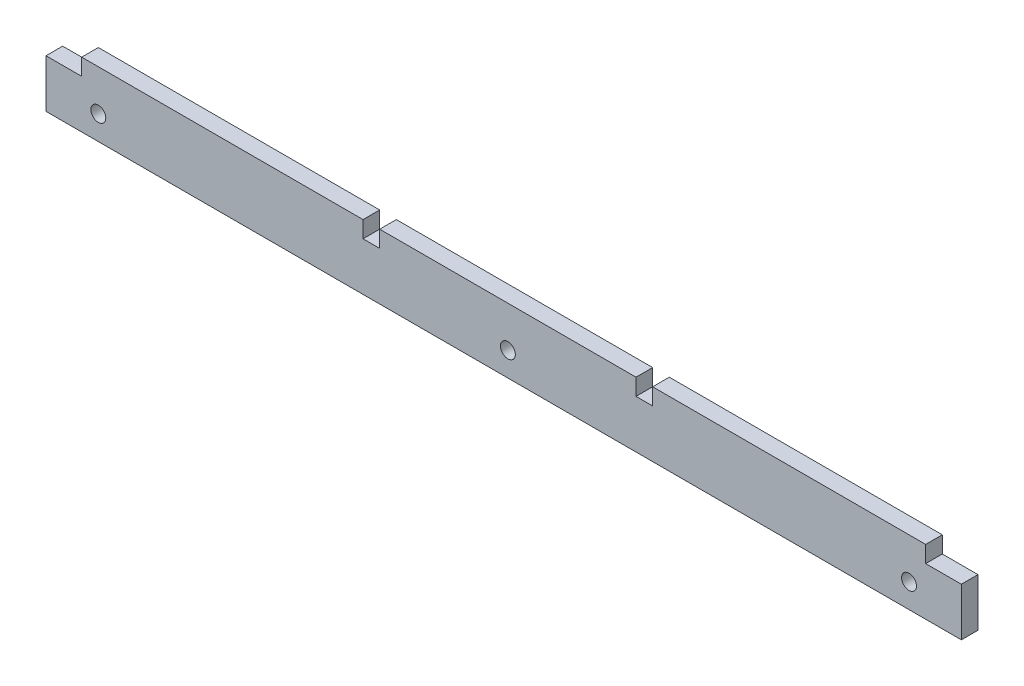
SolidWorks part; units mm, degrees
ref_plane "Front Plane" through (0, 0, 0) normal (0, 0, 1) x (1, 0, 0)
ref_plane "Top Plane" through (0, 0, 0) normal (0, 1, 0) x (1, 0, 0)
ref_plane "Right Plane" through (0, 0, 0) normal (1, 0, 0) x (0, 0, -1)
sketch "Sketch1" plane through (0, 0, 0) normal (0, 0, 1) x (1, 0, 0)
  line L0 (6075.4401, 2666.7324) -> (6075.4401, 2669.9074)
  line L1 (5914.4295, 2666.7324) -> (5914.4295, 2669.9074)
  line L2 (6023.3574, 2666.7324) -> (6023.3574, 2669.9074)
  line L3 (6020.1824, 2666.7324) -> (6020.1824, 2669.9074)
  line L4 (6082.2473, 2666.7324) -> (6075.4401, 2666.7324)
  line L5 (6023.3574, 2666.7324) -> (6020.1824, 2666.7324)
  line L6 (5971.2798, 2666.7324) -> (5968.1048, 2666.7324)
  line L7 (5914.4295, 2666.7324) -> (5907.6223, 2666.7324)
  line L8 (6075.4401, 2669.9074) -> (6023.3574, 2669.9074)
  line L9 (6020.1824, 2669.9074) -> (5971.2798, 2669.9074)
  line L10 (5968.1048, 2669.9074) -> (5914.4295, 2669.9074)
  line L11 (6082.2473, 2657.5376) -> (5907.6223, 2657.5376)
  line L12 (5971.2798, 2669.9074) -> (5971.2798, 2666.7324)
  line L13 (5968.1048, 2669.9074) -> (5968.1048, 2666.7324)
  line L14 (5907.6223, 2657.5376) -> (5907.6223, 2666.7324)
  line L15 (6082.2473, 2657.5376) -> (6082.2473, 2666.7324)
  circle A0 centre (5995.7311, 2662.135) radius 1.4224
  circle A1 centre (5917.6045, 2662.135) radius 1.4224
  circle A2 centre (6072.2651, 2662.135) radius 1.4224
extrude "Boss-Extrude1" add sketch "Sketch1" along normal blind 3.175
